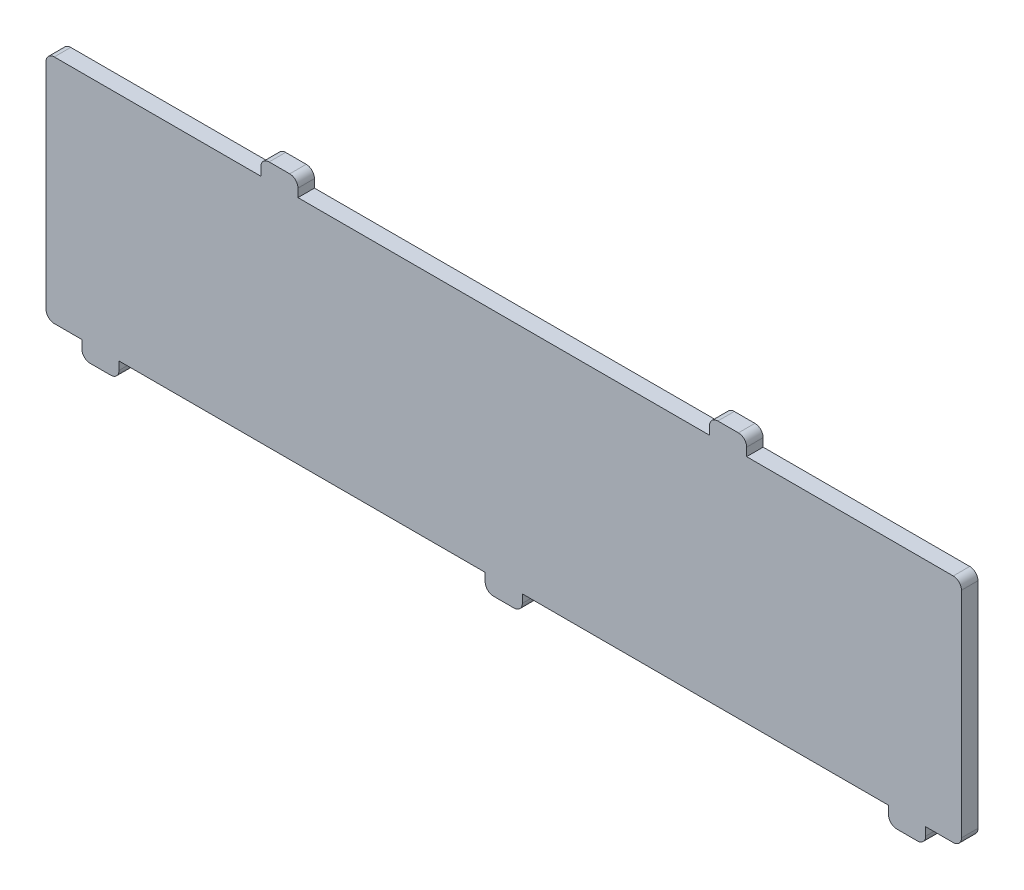
SolidWorks part; units mm, degrees
ref_plane "前基準面" through (0, 0, 0) normal (0, 0, 1) x (1, 0, 0)
ref_plane "上基準面" through (0, 0, 0) normal (0, 1, 0) x (1, 0, 0)
ref_plane "右基準面" through (0, 0, 0) normal (1, 0, 0) x (0, 0, -1)
sketch "Sketch1" plane through (0, 0, 0) normal (0, 0, 1) x (1, 0, 0)
  line L0 (0, 0) -> (0, -31.2064) construction
  line L1 (-55.5, 14) -> (55.5, 14)
  line L2 (-55.5, 14) -> (-55.5, -14)
  line L3 (-55.5, -14) -> (55.5, -14)
  line L4 (55.5, 14) -> (55.5, -14)
  line L5 (-55.5, 14) -> (55.5, -14) construction
  line L6 (-55.5, -14) -> (55.5, 14) construction
  line L7 (0, -31.2064) -> (0, 29.4941) construction
  line L8 (-2.25, -14) -> (2.25, -16) construction
  line L9 (-2.25, -14) -> (2.25, -14)
  line L10 (-2.25, -14) -> (-2.25, -16)
  line L11 (-2.25, -16) -> (2.25, -16)
  line L12 (2.25, -14) -> (2.25, -16)
  line L13 (-2.25, -16) -> (2.25, -14) construction
  line L14 (-51.15, -14) -> (-46.65, -16) construction
  line L15 (-51.15, -14) -> (-46.65, -14)
  line L16 (-51.15, -14) -> (-51.15, -16)
  line L17 (-51.15, -16) -> (-46.65, -16)
  line L18 (-46.65, -14) -> (-46.65, -16)
  line L19 (-46.65, -14) -> (-51.15, -16) construction
  line L20 (51.15, -16) -> (46.65, -16)
  line L21 (46.65, -14) -> (46.65, -16)
  line L22 (51.15, -14) -> (46.65, -14)
  line L23 (51.15, -14) -> (51.15, -16)
  line L24 (-48.9, -15) -> (-48.9, 18.4346) construction
  line L25 (0, -15.6032) -> (0, 17.9346) construction
  line L26 (46.65, -14) -> (51.15, -16) construction
  line L27 (51.15, -14) -> (46.65, -16) construction
  line L28 (-29.45, 16) -> (-24.95, 14) construction
  line L29 (-29.45, 14) -> (-24.95, 14)
  line L30 (-29.45, 14) -> (-29.45, 16)
  line L31 (-29.45, 16) -> (-24.95, 16)
  line L32 (-24.95, 14) -> (-24.95, 16)
  line L33 (-24.95, 16) -> (-29.45, 14) construction
  line L34 (29.45, 16) -> (24.95, 16)
  line L35 (24.95, 14) -> (24.95, 16)
  line L36 (29.45, 14) -> (24.95, 14)
  line L37 (29.45, 14) -> (29.45, 16)
  point P0 (0, 0)
  point P13 (0, -15)
  point P32 (-27.2, 15)
  dimension "D1" = 28
  dimension "D2" = 111
  dimension "D3" = 2
  dimension "D4" = 4.5
  dimension "D5" = 2
  dimension "D6" = 4.5
  dimension "D7" = 48.9
  dimension "D8" = 2
  dimension "D9" = 4.5
  dimension "D10" = 27.2
extrude "Boss-Extrude1" add sketch "Sketch1" along normal mid plane 2 contours L4 L1 L2 L3 | L12 L3 L10 L11 | L1 L37 L34 L35 | L1 L32 L31 L30 | L18 L17 L16 L15 | L23 L20 L21 L22
fillet "Fillet1" radius 1 14 edges at (55.5, -14, 0) (2.25, -16, 0) (-2.25, -16, 0) (-55.5, -14, 0) (-55.5, 14, 0) (-29.45, 16, 0) (-24.95, 16, 0) (24.95, 16, 0) (29.45, 16, 0) (55.5, 14, 0) (-51.15, -16, 0) (-46.65, -16, 0) (46.65, -16, 0) (51.15, -16, 0)
